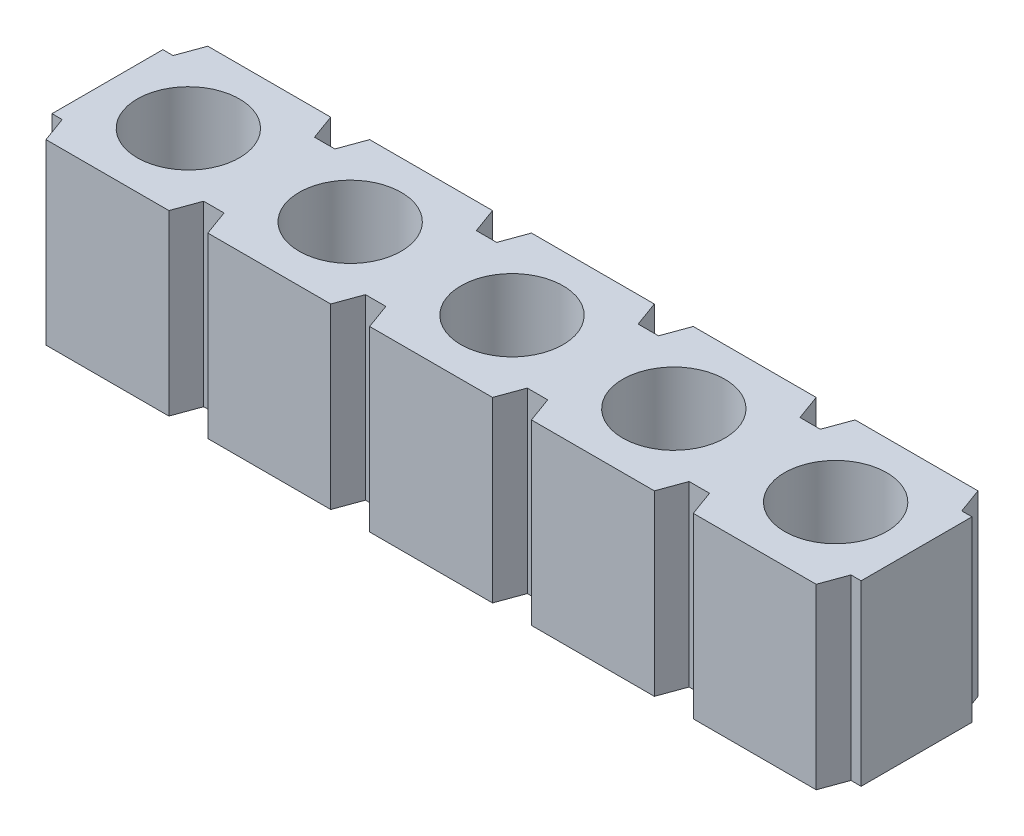
SolidWorks part; units mm, degrees
material "Nylon 46"
ref_plane "Front Plane" through (0, 0, 0) normal (0, 0, 1) x (1, 0, 0)
ref_plane "Top Plane" through (0, 0, 0) normal (0, 1, 0) x (1, 0, 0)
ref_plane "Right Plane" through (0, 0, 0) normal (1, 0, 0) x (0, 0, -1)
sketch "Sketch1" plane through (0, 0, 0) normal (0, 1, 0) x (1, 0, 0)
  line L0 (12.3944, 0.4) -> (12.2344, 0.4)
  line L1 (12.3944, 2.1399) -> (12.3944, 0.4)
  line L2 (-0.3056, 2.1399) -> (-0.1456, 2.1399)
  line L3 (-0.3056, 2.1399) -> (-0.3056, 0.4)
  line L4 (0, 0) -> (12.0887, 0)
  line L5 (0, 2.54) -> (-0.1456, 2.1399)
  line L6 (0, 0) -> (-0.1456, 0.4)
  line L7 (-0.3056, 0.4) -> (-0.1456, 0.4)
  line L9 (12.0887, 0) -> (12.2344, 0.4)
  line L10 (12.0887, 2.54) -> (12.2344, 2.1399)
  line L11 (12.3944, 2.1399) -> (12.2344, 2.1399)
  line L16 (12.0887, 2.54) -> (0, 2.54)
  dimension "D2" = 2.54
  dimension "D3" = 20
  dimension "D4" = 0.4
  dimension "D5" = 0.4
  dimension "D7" = 0.16
  dimension "INSLENGTH" = 12.7
extrude "Extrude1" add sketch "Sketch1" against normal blind 2.794
hole_wizard "Hole1" positions "3DSketch2" profile "Sketch3" legacy end condition through all
sketch3d "3DSketch2"
  line L2 (-0.3056, 0, -2.1399) -> (-0.3056, 0, -0.4) construction
  line L3 (12.0887, 0, -2.54) -> (0, 0, -2.54) construction
  point P0 (0.9644, 0, -1.27)
  dimension "D1" = 1.27
  dimension "D2" = 1.27
sketch "Sketch3" plane through (0.9644, 0, -1.27) normal (1, 0, 0) x (0, 0, 1)
  line L0 (0, 0) -> (0, 2.794)
  line L1 (0, 2.794) -> (0.8014, 2.794)
  line L2 (0.8014, 2.794) -> (0.8014, 0)
  line L3 (0.8014, 0) -> (0, 0)
  line L4 (0, 110) -> (0, -10) construction
  dimension "Diameter" = 1.6027
  dimension "Depth" = 2.794
sketch "Sketch4" plane through (0, 0, 0) normal (0, 1, 0) x (1, 0, 0)
  line L0 (1.9288, 0) -> (2.54, 0)
  line L2 (0, 0) -> (12.0887, 0) construction
  line L5 (2.0744, 0.4) -> (1.9288, 0)
  line L6 (2.3944, 0.4) -> (2.54, 0)
  line L7 (12.0887, 2.54) -> (0, 2.54) construction
  line L8 (2.0744, 0.4) -> (2.3944, 0.4)
  line L10 (2.0744, 2.1399) -> (2.3944, 2.1399)
  line L11 (2.3944, 2.1399) -> (2.54, 2.54)
  line L12 (2.0744, 2.1399) -> (1.9288, 2.54)
  line L13 (1.9288, 2.54) -> (2.54, 2.54)
  line L17 (-0.3056, 2.1399) -> (-0.3056, 0.4) construction
  dimension "D1" = 0.4
  dimension "D2" = 0.32
  dimension "D3" = 70
  dimension "D4" = 0.6112
  dimension "D5" = 0.4001
  dimension "D6" = 2.2344
extrude "Extrude2" cut sketch "Sketch4" against normal blind 2.794
pattern_linear "LPattern1" count 5 spacing 2.54 along (1, 0, 0) of "Hole1"
pattern_linear "LPattern2" count 63 spacing 2.54 along (1, 0, 0) of "Extrude2"
